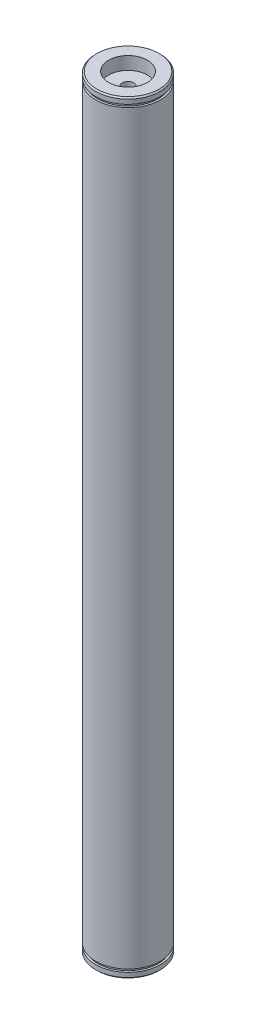
SolidWorks part; units mm, degrees
material "45"
ref_plane "前视基准面" through (0, 0, 0) normal (0, 0, 1) x (1, 0, 0)
ref_plane "上视基准面" through (0, 0, 0) normal (0, 1, 0) x (1, 0, 0)
ref_plane "右视基准面" through (0, 0, 0) normal (1, 0, 0) x (0, 0, -1)
sketch "草图1" plane through (0, 0, 0) normal (0, 1, 0) x (1, 0, 0)
  circle A0 centre (0, 0) radius 25
  dimension "D1" = 50
extrude "凸台-拉伸1" add sketch "草图1" along normal mid plane 591
sketch "草图2" plane through (0, 295.5, 0) normal (0, 1, 0) x (1, 0, 0)
  circle A0 centre (0, 0) radius 15
  dimension "D1" = 30
extrude "切除-拉伸1" cut sketch "草图2" against normal blind 10
hole_wizard "Ø8.0 (8) 直径孔1" positions "3D草图1" profile "草图4" hole size "Ø8.0" standard "GB"
sketch3d "3D草图1"
  line L0 (0, 295.5, 0) -> (0, -295.5, 0) construction
  line L1 (0, 285.5, 0) -> (0, 295.5, 0) construction
  point P0 (0, 285.5, 0)
  point P7 (0, 285.5, 0)
  point P9 (0, 285.5, 0)
sketch "草图4" plane through (0, 285.5, 0) normal (1, 0, 0) x (0, 0, 1)
  line L0 (0, 0) -> (0, 121.4034)
  line L1 (0, 121.4034) -> (4, 119)
  line L2 (4, 119) -> (4, 0)
  line L5 (4, 0) -> (0, 0)
  line L10 (0, 121.4034) -> (-4, 119) construction
  line L11 (0, -6.35) -> (0, 107.95) construction
  dimension "孔直径" = 8
  dimension "孔深度" = 119
  dimension "导头角度" = 118
sketch "草图5" plane through (0, 0, 0) normal (0, 0, 1) x (1, 0, 0)
  line L0 (0, 295.5) -> (0, -295.5) construction
  line L1 (25, 295.5) -> (-25, 295.5) construction
  line L2 (-25, -295.5) -> (25, -295.5) construction
  circle A0 centre (0, 170.5) radius 3
  dimension "D1" = 6
  dimension "D2" = 125
extrude "切除-拉伸2" cut sketch "草图5" against normal blind 100
hole_wizard "M10x1.0 螺纹孔1" positions "草图6" profile "草图7" tap size "M10x1.0" standard "GB"
sketch "草图6" plane through (0, 285.5, 0) normal (0, 1, 0) x (1, 0, 0)
  point P0 (0, 0)
sketch "草图7" plane through (0, 285.5, 0) normal (1, 0, 0) x (0, 0, 1)
  line L0 (0, 0) -> (0, 27.7039)
  line L1 (0, 27.7039) -> (4.5, 25)
  line L2 (4.5, 25) -> (4.5, 0)
  line L5 (4.5, 0) -> (0, 0)
  line L10 (0, 27.7039) -> (-4.5, 25) construction
  line L11 (0, -6.35) -> (0, 107.95) construction
  dimension "螺纹孔钻头直径" = 9
  dimension "螺纹孔钻头深度" = 25
  dimension "导头角度" = 118
cosmetic thread "孔螺蚊线2" parameters "D1"=20, "D2"=10
sketch "草图8" plane through (0, -295.5, 0) normal (0, -1, 0) x (1, 0, 0)
  circle A0 centre (0, 0) radius 15
  dimension "D1" = 30
extrude "切除-拉伸3" cut sketch "草图8" against normal blind 10
hole_wizard "Ø8.0 (8) 直径孔2" positions "3D草图2" profile "草图9" hole size "Ø8.0" standard "GB"
sketch3d "3D草图2"
  line L0 (0, -285.5, 0) -> (0, -295.5, 0) construction
  point P0 (0, -285.5, 0)
sketch "草图9" plane through (0, -285.5, 0) normal (1, 0, 0) x (0, 0, -1)
  line L0 (0, 0) -> (0, 121.4034)
  line L1 (0, 121.4034) -> (4, 119)
  line L2 (4, 119) -> (4, 0)
  line L5 (4, 0) -> (0, 0)
  line L10 (0, 121.4034) -> (-4, 119) construction
  line L11 (0, -6.35) -> (0, 107.95) construction
  dimension "孔直径" = 8
  dimension "孔深度" = 119
  dimension "导头角度" = 118
hole_wizard "M10x1.0 螺纹孔2" positions "草图10" profile "草图11" tap size "M10x1.0" standard "GB"
sketch "草图10" plane through (0, -285.5, 0) normal (0, -1, 0) x (-1, 0, 0)
  point P0 (0, 0)
sketch "草图11" plane through (0, -285.5, 0) normal (1, 0, 0) x (0, 0, -1)
  line L0 (0, 0) -> (0, 27.7039)
  line L1 (0, 27.7039) -> (4.5, 25)
  line L2 (4.5, 25) -> (4.5, 0)
  line L5 (4.5, 0) -> (0, 0)
  line L10 (0, 27.7039) -> (-4.5, 25) construction
  line L11 (0, -6.35) -> (0, 107.95) construction
  dimension "螺纹孔钻头直径" = 9
  dimension "螺纹孔钻头深度" = 25
  dimension "导头角度" = 118
cosmetic thread "孔螺蚊线1" parameters "D1"=20, "D2"=10
sketch "草图12" plane through (0, 0, 0) normal (0, 0, 1) x (1, 0, 0)
  line L0 (0, 0) -> (0, -295.5) construction
  line L1 (-25, -295.5) -> (25, -295.5) construction
  circle A0 centre (0, -170.5) radius 3
  dimension "D1" = 6
  dimension "D2" = 125
extrude "切除-拉伸4" cut sketch "草图12" against normal blind 51
chamfer "倒角1" distance 1 angle 45 2 edges at (0, -295.5, 25) (0, 295.5, 25)
sketch "草图14" plane through (0, 0, 0) normal (1, 0, 0) x (0, 0, -1)
  line L0 (0, 0) -> (0, 428.7278) construction
  line L1 (0, 0) -> (0, -399.4812) construction
  line L2 (25, 291) -> (23.5, 291)
  line L3 (25, 173.5) -> (25, 294.5) construction
  line L4 (23.5, 291) -> (23.5, 288.8)
  line L5 (23.5, 288.8) -> (25, 288.8)
  line L6 (24, 295.5) -> (-24, 295.5) construction
  line L7 (25, 291) -> (25, 288.8)
  line L8 (25, -291) -> (23.5, -291)
  line L9 (23.5, -291) -> (23.5, -288.8)
  line L10 (23.5, -288.8) -> (25, -288.8)
  line L11 (25, -288.8) -> (25, -291)
  line L12 (-24, -295.5) -> (24, -295.5) construction
  dimension "D1" = 4.5
  dimension "D2" = 2.2
  dimension "D3" = 1.5
  dimension "D4" = 4.5
  dimension "D5" = 2.2
  dimension "D6" = 1.5
revolve "切除-旋转1" cut sketch "草图14" angle 360 about L0
